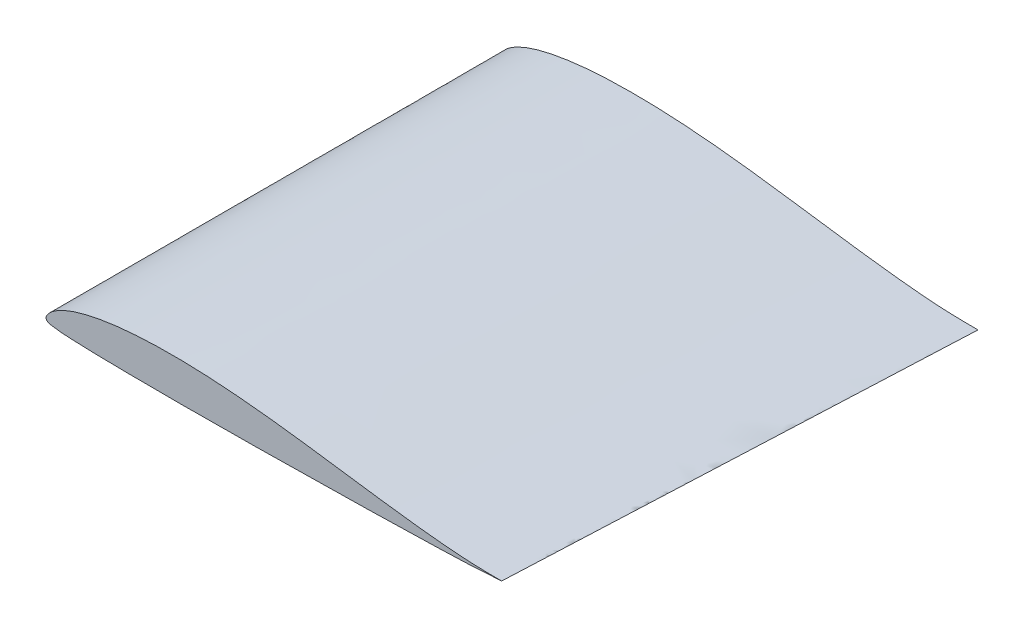
SolidWorks part; units mm, degrees
ref_plane "Front Plane" through (0, 0, 0) normal (0, 0, 1) x (1, 0, 0)
ref_plane "Top Plane" through (0, 0, 0) normal (0, 1, 0) x (1, 0, 0)
ref_plane "Right Plane" through (0, 0, 0) normal (1, 0, 0) x (0, 0, -1)
curve "Curve1"
  spline degree 3 poles (114.2372, -0.0369, 0) (115.1931, 0.0052, 0) (114.2229, -0.0046, 0) (113.4181, 0.0003, 0) (111.4454, 0.0187, 0) (108.9994, 0.0806, 0) (105.7801, 0.2031, 0) (101.978, 0.4673, 0) (97.6315, 0.881, 0) (92.8438, 1.4274, 0) (87.693, 2.0622, 0) (82.2613, 2.7949, 0) (76.6289, 3.5822, 0) (70.8754, 4.4083, 0) (65.0695, 5.2045, 0) (59.2726, 5.965, 0) (53.5354, 6.6121, 0) (47.902, 7.1479, 0) (42.4207, 7.5381, 0) (37.1257, 7.7843, 0) (32.0601, 7.8639, 0) (27.2609, 7.7997, 0) (22.7643, 7.5854, 0) (18.6066, 7.224, 0) (14.8196, 6.7174, 0) (11.4312, 6.1029, 0) (8.4633, 5.3595, 0) (5.93, 4.5232, 0) (3.8402, 3.6114, 0) (2.2031, 2.6805, 0) (0.9971, 1.7194, 0) (0.3061, 0.8447, 0) (-0.1539, -0.0168, 0) (0.4411, -0.7838, 0) (1.6303, -0.9762, 0) (3.345, -1.2471, 0) (5.7413, -1.3854, 0) (8.741, -1.531, 0) (12.3236, -1.6134, 0) (16.4261, -1.712, 0) (20.9966, -1.764, 0) (25.9799, -1.8041, 0) (31.3167, -1.8262, 0) (36.95, -1.8119, 0) (42.8101, -1.7838, 0) (48.8334, -1.73, 0) (54.9501, -1.6735, 0) (61.0935, -1.5952, 0) (67.1933, -1.4881, 0) (73.1769, -1.3978, 0) (78.98, -1.2712, 0) (84.5334, -1.153, 0) (89.7769, -1.0374, 0) (94.647, -0.905, 0) (99.0896, -0.7783, 0) (103.0556, -0.6463, 0) (106.4883, -0.5296, 0) (109.3913, -0.3707, 0) (111.629, -0.2442, 0) (113.4671, -0.0996, 0) (114.2372, -0.0369, 0) (115.1931, 0.0052, 0) (114.2229, -0.0046, 0) knots -0.013468 -0.006107 -0.001548 0 0.001545 0.006224 0.014036 0.024855 0.038644 0.055164 0.074045 0.09482 0.117223 0.140866 0.165395 0.190452 0.21571 0.240854 0.265734 0.290048 0.313714 0.336486 0.358293 0.37894 0.398278 0.416247 0.43266 0.44746 0.460566 0.472022 0.481784 0.489844 0.496307 0.501261 0.504695 0.507386 0.51219 0.519693 0.52998 0.542956 0.558414 0.576102 0.595805 0.617266 0.640272 0.664523 0.689804 0.715729 0.742084 0.768569 0.79484 0.82064 0.845625 0.869581 0.892164 0.91316 0.932311 0.949403 0.964221 0.976642 0.986532 0.993893 0.998452 1 1.001545 1.006224 1.014036 periodic
curve "Curve2"
  spline degree 3 poles (109.2695, -0.032, 0) (110.1862, 0.0049, 0) (109.2536, -0.0064, 0) (108.4853, 0.002, 0) (106.5995, 0.014, 0) (104.2599, 0.0712, 0) (101.179, 0.2009, 0) (97.5427, 0.452, 0) (93.3846, 0.8435, 0) (88.8052, 1.362, 0) (83.8804, 1.9786, 0) (78.6866, 2.6775, 0) (73.2995, 3.4307, 0) (67.7952, 4.2152, 0) (62.2412, 4.9847, 0) (56.6955, 5.6975, 0) (51.2078, 6.3228, 0) (45.8215, 6.8336, 0) (40.5778, 7.2116, 0) (35.5143, 7.4443, 0) (30.6685, 7.5275, 0) (26.0768, 7.4635, 0) (21.7757, 7.2552, 0) (17.7989, 6.9092, 0) (14.177, 6.4302, 0) (10.9351, 5.832, 0) (8.0947, 5.1223, 0) (5.6702, 4.3272, 0) (3.6698, 3.4606, 0) (2.1091, 2.5615, 0) (0.9527, 1.648, 0) (0.2925, 0.8103, 0) (-0.1445, -0.0134, 0) (0.4215, -0.7518, 0) (1.5614, -0.9277, 0) (3.1964, -1.1996, 0) (5.4899, -1.3252, 0) (8.3594, -1.4573, 0) (11.7865, -1.5532, 0) (15.712, -1.6328, 0) (20.0859, -1.6935, 0) (24.8533, -1.7305, 0) (29.9585, -1.7453, 0) (35.3441, -1.7366, 0) (40.949, -1.7075, 0) (46.7101, -1.6601, 0) (52.5621, -1.5957, 0) (58.4383, -1.5196, 0) (64.2724, -1.4291, 0) (69.9971, -1.3294, 0) (75.5481, -1.2224, 0) (80.8615, -1.1084, 0) (85.8767, -0.9906, 0) (90.5362, -0.8694, 0) (94.7848, -0.7467, 0) (98.5777, -0.6218, 0) (101.8584, -0.4962, 0) (104.6359, -0.3663, 0) (106.7737, -0.2243, 0) (108.5325, -0.0997, 0) (109.2695, -0.032, 0) (110.1862, 0.0049, 0) (109.2536, -0.0064, 0) knots -0.013463 -0.006118 -0.001552 0 0.001565 0.006239 0.014019 0.024861 0.03866 0.055174 0.074046 0.094837 0.117226 0.140856 0.165386 0.190451 0.215702 0.240867 0.265719 0.290052 0.313696 0.336484 0.35828 0.378929 0.398292 0.416236 0.43265 0.447456 0.460592 0.47203 0.481779 0.489853 0.496315 0.501246 0.504685 0.507404 0.512183 0.519673 0.529968 0.542948 0.5584 0.576099 0.595811 0.617283 0.64028 0.664535 0.689783 0.715733 0.742093 0.768567 0.794844 0.820639 0.845644 0.869584 0.892183 0.913178 0.932328 0.949411 0.96423 0.976629 0.986537 0.993882 0.998448 1 1.001565 1.006239 1.014019 periodic
sketch "Sketch1" plane through (0, 0, 0) normal (0, 0, 1) x (1, 0, 0)
  spline S0 degree 3 poles (114.2372, -0.0369) (115.1931, 0.0052) (114.2229, -0.0046) (113.4181, 0.0003) (111.4454, 0.0187) (108.9994, 0.0806) (105.7801, 0.2031) (101.978, 0.4673) (97.6315, 0.881) (92.8438, 1.4274) (87.693, 2.0622) (82.2613, 2.7949) (76.6289, 3.5822) (70.8754, 4.4083) (65.0695, 5.2045) (59.2726, 5.965) (53.5354, 6.6121) (47.902, 7.1479) (42.4207, 7.5381) (37.1257, 7.7843) (32.0601, 7.8639) (27.2609, 7.7997) (22.7643, 7.5854) (18.6066, 7.224) (14.8196, 6.7174) (11.4312, 6.1029) (8.4633, 5.3595) (5.93, 4.5232) (3.8402, 3.6114) (2.2031, 2.6805) (0.9971, 1.7194) (0.3061, 0.8447) (-0.1539, -0.0168) (0.4411, -0.7838) (1.6303, -0.9762) (3.345, -1.2471) (5.7413, -1.3854) (8.741, -1.531) (12.3236, -1.6134) (16.4261, -1.712) (20.9966, -1.764) (25.9799, -1.8041) (31.3167, -1.8262) (36.95, -1.8119) (42.8101, -1.7838) (48.8334, -1.73) (54.9501, -1.6735) (61.0935, -1.5952) (67.1933, -1.4881) (73.1769, -1.3978) (78.98, -1.2712) (84.5334, -1.153) (89.7769, -1.0374) (94.647, -0.905) (99.0896, -0.7783) (103.0556, -0.6463) (106.4883, -0.5296) (109.3913, -0.3707) (111.629, -0.2442) (113.4671, -0.0996) (114.2372, -0.0369) (115.1931, 0.0052) (114.2229, -0.0046) knots -0.013468 -0.006107 -0.001548 0 0.001545 0.006224 0.014036 0.024855 0.038644 0.055164 0.074045 0.09482 0.117223 0.140866 0.165395 0.190452 0.21571 0.240854 0.265734 0.290048 0.313714 0.336486 0.358293 0.37894 0.398278 0.416247 0.43266 0.44746 0.460566 0.472022 0.481784 0.489844 0.496307 0.501261 0.504695 0.507386 0.51219 0.519693 0.52998 0.542956 0.558414 0.576102 0.595805 0.617266 0.640272 0.664523 0.689804 0.715729 0.742084 0.768569 0.79484 0.82064 0.845625 0.869581 0.892164 0.91316 0.932311 0.949403 0.964221 0.976642 0.986532 0.993893 0.998452 1 1.001545 1.006224 1.014036 only from (115, 0) to (115, 0) construction
  spline S1 degree 3 poles (114.2372, -0.0369) (115.1931, 0.0052) (114.2229, -0.0046) (113.4181, 0.0003) (111.4454, 0.0187) (108.9994, 0.0806) (105.7801, 0.2031) (101.978, 0.4673) (97.6315, 0.881) (92.8438, 1.4274) (87.693, 2.0622) (82.2613, 2.7949) (76.6289, 3.5822) (70.8754, 4.4083) (65.0695, 5.2045) (59.2726, 5.965) (53.5354, 6.6121) (47.902, 7.1479) (42.4207, 7.5381) (37.1257, 7.7843) (32.0601, 7.8639) (27.2609, 7.7997) (22.7643, 7.5854) (18.6066, 7.224) (14.8196, 6.7174) (11.4312, 6.1029) (8.4633, 5.3595) (5.93, 4.5232) (3.8402, 3.6114) (2.2031, 2.6805) (0.9971, 1.7194) (0.3061, 0.8447) (-0.1539, -0.0168) (0.4411, -0.7838) (1.6303, -0.9762) (3.345, -1.2471) (5.7413, -1.3854) (8.741, -1.531) (12.3236, -1.6134) (16.4261, -1.712) (20.9966, -1.764) (25.9799, -1.8041) (31.3167, -1.8262) (36.95, -1.8119) (42.8101, -1.7838) (48.8334, -1.73) (54.9501, -1.6735) (61.0935, -1.5952) (67.1933, -1.4881) (73.1769, -1.3978) (78.98, -1.2712) (84.5334, -1.153) (89.7769, -1.0374) (94.647, -0.905) (99.0896, -0.7783) (103.0556, -0.6463) (106.4883, -0.5296) (109.3913, -0.3707) (111.629, -0.2442) (113.4671, -0.0996) (114.2372, -0.0369) (115.1931, 0.0052) (114.2229, -0.0046) knots -0.013468 -0.006107 -0.001548 0 0.001545 0.006224 0.014036 0.024855 0.038644 0.055164 0.074045 0.09482 0.117223 0.140866 0.165395 0.190452 0.21571 0.240854 0.265734 0.290048 0.313714 0.336486 0.358293 0.37894 0.398278 0.416247 0.43266 0.44746 0.460566 0.472022 0.481784 0.489844 0.496307 0.501261 0.504695 0.507386 0.51219 0.519693 0.52998 0.542956 0.558414 0.576102 0.595805 0.617266 0.640272 0.664523 0.689804 0.715729 0.742084 0.768569 0.79484 0.82064 0.845625 0.869581 0.892164 0.91316 0.932311 0.949403 0.964221 0.976642 0.986532 0.993893 0.998452 1 1.001545 1.006224 1.014036 only from (115, 0) to (115, 0)
ref_plane "Plane1" through (0, 0, 110) normal (0, 0, 1) x (1, 0, 0)
sketch "Sketch2" plane through (0, 0, 110) normal (0, 0, 1) x (1, 0, 0)
  spline S0 degree 3 poles (109.2695, -0.032) (110.1862, 0.0049) (109.2536, -0.0064) (108.4853, 0.002) (106.5995, 0.014) (104.2599, 0.0712) (101.179, 0.2009) (97.5427, 0.452) (93.3846, 0.8435) (88.8052, 1.362) (83.8804, 1.9786) (78.6866, 2.6775) (73.2995, 3.4307) (67.7952, 4.2152) (62.2412, 4.9847) (56.6955, 5.6975) (51.2078, 6.3228) (45.8215, 6.8336) (40.5778, 7.2116) (35.5143, 7.4443) (30.6685, 7.5275) (26.0768, 7.4635) (21.7757, 7.2552) (17.7989, 6.9092) (14.177, 6.4302) (10.9351, 5.832) (8.0947, 5.1223) (5.6702, 4.3272) (3.6698, 3.4606) (2.1091, 2.5615) (0.9527, 1.648) (0.2925, 0.8103) (-0.1445, -0.0134) (0.4215, -0.7518) (1.5614, -0.9277) (3.1964, -1.1996) (5.4899, -1.3252) (8.3594, -1.4573) (11.7865, -1.5532) (15.712, -1.6328) (20.0859, -1.6935) (24.8533, -1.7305) (29.9585, -1.7453) (35.3441, -1.7366) (40.949, -1.7075) (46.7101, -1.6601) (52.5621, -1.5957) (58.4383, -1.5196) (64.2724, -1.4291) (69.9971, -1.3294) (75.5481, -1.2224) (80.8615, -1.1084) (85.8767, -0.9906) (90.5362, -0.8694) (94.7848, -0.7467) (98.5777, -0.6218) (101.8584, -0.4962) (104.6359, -0.3663) (106.7737, -0.2243) (108.5325, -0.0997) (109.2695, -0.032) (110.1862, 0.0049) (109.2536, -0.0064) knots -0.013463 -0.006118 -0.001552 0 0.001565 0.006239 0.014019 0.024861 0.03866 0.055174 0.074046 0.094837 0.117226 0.140856 0.165386 0.190451 0.215702 0.240867 0.265719 0.290052 0.313696 0.336484 0.35828 0.378929 0.398292 0.416236 0.43265 0.447456 0.460592 0.47203 0.481779 0.489853 0.496315 0.501246 0.504685 0.507404 0.512183 0.519673 0.529968 0.542948 0.5584 0.576099 0.595811 0.617283 0.64028 0.664535 0.689783 0.715733 0.742093 0.768567 0.794844 0.820639 0.845644 0.869584 0.892183 0.913178 0.932328 0.949411 0.96423 0.976629 0.986537 0.993882 0.998448 1 1.001565 1.006239 1.014019 only from (110, 0) to (110, 0) construction
  spline S1 degree 3 poles (109.2695, -0.032) (110.1862, 0.0049) (109.2536, -0.0064) (108.4853, 0.002) (106.5995, 0.014) (104.2599, 0.0712) (101.179, 0.2009) (97.5427, 0.452) (93.3846, 0.8435) (88.8052, 1.362) (83.8804, 1.9786) (78.6866, 2.6775) (73.2995, 3.4307) (67.7952, 4.2152) (62.2412, 4.9847) (56.6955, 5.6975) (51.2078, 6.3228) (45.8215, 6.8336) (40.5778, 7.2116) (35.5143, 7.4443) (30.6685, 7.5275) (26.0768, 7.4635) (21.7757, 7.2552) (17.7989, 6.9092) (14.177, 6.4302) (10.9351, 5.832) (8.0947, 5.1223) (5.6702, 4.3272) (3.6698, 3.4606) (2.1091, 2.5615) (0.9527, 1.648) (0.2925, 0.8103) (-0.1445, -0.0134) (0.4215, -0.7518) (1.5614, -0.9277) (3.1964, -1.1996) (5.4899, -1.3252) (8.3594, -1.4573) (11.7865, -1.5532) (15.712, -1.6328) (20.0859, -1.6935) (24.8533, -1.7305) (29.9585, -1.7453) (35.3441, -1.7366) (40.949, -1.7075) (46.7101, -1.6601) (52.5621, -1.5957) (58.4383, -1.5196) (64.2724, -1.4291) (69.9971, -1.3294) (75.5481, -1.2224) (80.8615, -1.1084) (85.8767, -0.9906) (90.5362, -0.8694) (94.7848, -0.7467) (98.5777, -0.6218) (101.8584, -0.4962) (104.6359, -0.3663) (106.7737, -0.2243) (108.5325, -0.0997) (109.2695, -0.032) (110.1862, 0.0049) (109.2536, -0.0064) knots -0.013463 -0.006118 -0.001552 0 0.001565 0.006239 0.014019 0.024861 0.03866 0.055174 0.074046 0.094837 0.117226 0.140856 0.165386 0.190451 0.215702 0.240867 0.265719 0.290052 0.313696 0.336484 0.35828 0.378929 0.398292 0.416236 0.43265 0.447456 0.460592 0.47203 0.481779 0.489853 0.496315 0.501246 0.504685 0.507404 0.512183 0.519673 0.529968 0.542948 0.5584 0.576099 0.595811 0.617283 0.64028 0.664535 0.689783 0.715733 0.742093 0.768567 0.794844 0.820639 0.845644 0.869584 0.892183 0.913178 0.932328 0.949411 0.96423 0.976629 0.986537 0.993882 0.998448 1 1.001565 1.006239 1.014019 only from (110, 0) to (110, 0)
loft "Loft1" add profiles "Sketch1", "Sketch2"
sketch3d "3DSketch1"
  line L0 (109.958, 0.0012, 110) -> (-0.0041, 0.0606, 110)
  spline S0 degree 3 poles (-0.0041, 0.0606, 110) (0.0315, -1.565, -338.6935) (-0.069, 4.911, 79.3992) (0.056, 12.511, -112.5454) knots 0 0 0 0 1 1 1 1
  spline S1 degree 3 poles (109.2695, -0.032, 110) (110.1862, 0.0049, 110) (109.2536, -0.0064, 110) (108.4853, 0.002, 110) (106.5995, 0.014, 110) (104.2599, 0.0712, 110) (101.179, 0.2009, 110) (97.5427, 0.452, 110) (93.3846, 0.8435, 110) (88.8052, 1.362, 110) (83.8804, 1.9786, 110) (78.6866, 2.6775, 110) (73.2995, 3.4307, 110) (67.7952, 4.2152, 110) (62.2412, 4.9847, 110) (56.6955, 5.6975, 110) (51.2078, 6.3228, 110) (45.8215, 6.8336, 110) (40.5778, 7.2116, 110) (35.5143, 7.4443, 110) (30.6685, 7.5275, 110) (26.0768, 7.4635, 110) (21.7757, 7.2552, 110) (17.7989, 6.9092, 110) (14.177, 6.4302, 110) (10.9351, 5.832, 110) (8.0947, 5.1223, 110) (5.6702, 4.3272, 110) (3.6698, 3.4606, 110) (2.1091, 2.5615, 110) (0.9527, 1.648, 110) (0.2925, 0.8103, 110) (-0.1445, -0.0134, 110) (0.4215, -0.7518, 110) (1.5614, -0.9277, 110) (3.1964, -1.1996, 110) (5.4899, -1.3252, 110) (8.3594, -1.4573, 110) (11.7865, -1.5532, 110) (15.712, -1.6328, 110) (20.0859, -1.6935, 110) (24.8533, -1.7305, 110) (29.9585, -1.7453, 110) (35.3441, -1.7366, 110) (40.949, -1.7075, 110) (46.7101, -1.6601, 110) (52.5621, -1.5957, 110) (58.4383, -1.5196, 110) (64.2724, -1.4291, 110) (69.9971, -1.3294, 110) (75.5481, -1.2224, 110) (80.8615, -1.1084, 110) (85.8767, -0.9906, 110) (90.5362, -0.8694, 110) (94.7848, -0.7467, 110) (98.5777, -0.6218, 110) (101.8584, -0.4962, 110) (104.6359, -0.3663, 110) (106.7737, -0.2243, 110) (108.5325, -0.0997, 110) (109.2695, -0.032, 110) (110.1862, 0.0049, 110) (109.2536, -0.0064, 110) knots -0.013463 -0.006118 -0.001552 0 0.001565 0.006239 0.014019 0.024861 0.03866 0.055174 0.074046 0.094837 0.117226 0.140856 0.165386 0.190451 0.215702 0.240867 0.265719 0.290052 0.313696 0.336484 0.35828 0.378929 0.398292 0.416236 0.43265 0.447456 0.460592 0.47203 0.481779 0.489853 0.496315 0.501246 0.504685 0.507404 0.512183 0.519673 0.529968 0.542948 0.5584 0.576099 0.595811 0.617283 0.64028 0.664535 0.689783 0.715733 0.742093 0.768567 0.794844 0.820639 0.845644 0.869584 0.892183 0.913178 0.932328 0.949411 0.96423 0.976629 0.986537 0.993882 0.998448 1 1.001565 1.006239 1.014019 only from (110, 0, 110) to (110, 0, 110) construction
  spline S2 degree 3 poles (109.2536, -0.0064, 110) (110.1862, 0.0049, 110) (109.2695, -0.032, 110) (108.5325, -0.0997, 110) (106.7737, -0.2243, 110) (104.6359, -0.3663, 110) (101.8584, -0.4962, 110) (98.5777, -0.6218, 110) (94.7848, -0.7467, 110) (90.5362, -0.8694, 110) (85.8767, -0.9906, 110) (80.8615, -1.1084, 110) (75.5481, -1.2224, 110) (69.9971, -1.3294, 110) (64.2724, -1.4291, 110) (58.4383, -1.5196, 110) (52.5621, -1.5957, 110) (46.7101, -1.6601, 110) (40.949, -1.7075, 110) (35.3441, -1.7366, 110) (29.9585, -1.7453, 110) (24.8533, -1.7305, 110) (20.0859, -1.6935, 110) (15.712, -1.6328, 110) (11.7865, -1.5532, 110) (8.3594, -1.4573, 110) (5.4899, -1.3252, 110) (3.1964, -1.1996, 110) (1.5614, -0.9277, 110) (0.4215, -0.7518, 110) (-0.1445, -0.0134, 110) (0.2925, 0.8103, 110) (0.9527, 1.648, 110) (2.1091, 2.5615, 110) (3.6698, 3.4606, 110) (5.6702, 4.3272, 110) (8.0947, 5.1223, 110) (10.9351, 5.832, 110) (14.177, 6.4302, 110) (17.7989, 6.9092, 110) (21.7757, 7.2552, 110) (26.0768, 7.4635, 110) (30.6685, 7.5275, 110) (35.5143, 7.4443, 110) (40.5778, 7.2116, 110) (45.8215, 6.8336, 110) (51.2078, 6.3228, 110) (56.6955, 5.6975, 110) (62.2412, 4.9847, 110) (67.7952, 4.2152, 110) (73.2995, 3.4307, 110) (78.6866, 2.6775, 110) (83.8804, 1.9786, 110) (88.8052, 1.362, 110) (93.3846, 0.8435, 110) (97.5427, 0.452, 110) (101.179, 0.2009, 110) (104.2599, 0.0712, 110) (106.5995, 0.014, 110) (108.4853, 0.002, 110) (109.2536, -0.0064, 110) (110.1862, 0.0049, 110) (109.2695, -0.032, 110) knots -0.014019 -0.006239 -0.001565 0 0.001552 0.006118 0.013463 0.023371 0.03577 0.050589 0.067672 0.086822 0.107817 0.130416 0.154356 0.179361 0.205156 0.231433 0.257907 0.284267 0.310217 0.335465 0.35972 0.382717 0.404189 0.423901 0.4416 0.457052 0.470032 0.480327 0.487817 0.492596 0.495315 0.498754 0.503685 0.510147 0.518221 0.52797 0.539408 0.552544 0.56735 0.583764 0.601708 0.621071 0.64172 0.663516 0.686304 0.709948 0.734281 0.759133 0.784298 0.809549 0.834614 0.859144 0.882774 0.905163 0.925954 0.944826 0.96134 0.975139 0.985981 0.993761 0.998435 1 1.001552 1.006118 1.013463 only from (110, 0, 110) to (110, 0, 110) construction
  spline S3 degree 3 poles (0.056, 12.511, -112.5454) (36.7587, 17.2094, -112.9091) (72.3737, 14.4641, -114.505) (106.8822, 2.4299, -108.2168) knots 0 0 0 0 1 1 1 1
  spline S4 degree 2 poles (109.958, 0.0012, 110) (178.3212, -44.3264, -37.5467) (106.8822, 2.4299, -108.2168) knots 0 0 0 1 1 1
  spline S5 degree 3 poles (-0.0041, 0.0606, 110) (-0.0059, 0.0222, 110) (0.0056, -0.2093, 110) (0.4215, -0.7518, 110) (1.5614, -0.9277, 110) (3.1964, -1.1996, 110) (5.4899, -1.3252, 110) (8.3594, -1.4573, 110) (11.7865, -1.5532, 110) (15.712, -1.6328, 110) (20.0859, -1.6935, 110) (24.8533, -1.7305, 110) (29.9585, -1.7453, 110) (35.3441, -1.7366, 110) (40.949, -1.7075, 110) (46.7101, -1.6601, 110) (52.5621, -1.5957, 110) (58.4383, -1.5196, 110) (64.2724, -1.4291, 110) (69.9971, -1.3294, 110) (75.5481, -1.2224, 110) (80.8615, -1.1084, 110) (85.8767, -0.9906, 110) (90.5362, -0.8694, 110) (94.7848, -0.7467, 110) (98.5777, -0.6218, 110) (101.8584, -0.4962, 110) (104.6359, -0.3663, 110) (106.7737, -0.2243, 110) (108.5325, -0.0997, 110) (109.2695, -0.032, 110) (110.1862, 0.0049, 110) (109.2536, -0.0064, 110) (108.8452, -0.0019, 110) (108.45, 0.0014, 110) (108.3661, 0.0021, 110) knots 0.504147 0.504147 0.504147 0.504147 0.504685 0.507404 0.512183 0.519673 0.529968 0.542948 0.5584 0.576099 0.595811 0.617283 0.64028 0.664535 0.689783 0.715733 0.742093 0.768567 0.794844 0.820639 0.845644 0.869584 0.892183 0.913178 0.932328 0.949411 0.96423 0.976629 0.986537 0.993882 0.998448 1 1.001565 1.006239 1.007451 1.007451 1.007451 1.007451
sketch "Sketch4" plane through (0, 0, 0) normal (0, 0, -1) x (-1, 0, 0)
  circle A0 centre (-10.5, 2) radius 2.6
  circle A1 centre (-57, 2.1) radius 3.1
  dimension "D1" = 5.2
  dimension "D2" = 6.2
  dimension "D3" = 10.5
  dimension "D4" = 2
  dimension "D5" = 2.1
  dimension "D6" = 57
extrude "Cut-Extrude1" cut sketch "Sketch4" against normal blind 5.2
sketch "Sketch5" plane through (0, 0, 0) normal (0, 0, -1) x (-1, 0, 0)
  line L1 (-25.95, 5.8) -> (-16.05, 5.8)
  line L2 (-25.95, 5.8) -> (-25.95, -0.2)
  line L3 (-25.95, -0.2) -> (-16.05, -0.2)
  line L4 (-16.05, 5.8) -> (-16.05, -0.2)
  line L5 (-25.95, 5.8) -> (-16.05, -0.2) construction
  line L6 (-25.95, -0.2) -> (-16.05, 5.8) construction
  line L7 (-50.75, 6) -> (-41.25, 6)
  line L8 (-50.75, 6) -> (-50.75, 0)
  line L9 (-50.75, 0) -> (-41.25, 0)
  line L10 (-41.25, 6) -> (-41.25, 0)
  line L11 (-50.75, 6) -> (-41.25, 0) construction
  line L12 (-50.75, 0) -> (-41.25, 6) construction
  point P0 (-21, 2.8)
  point P5 (-46, 3)
  dimension "D1" = 6
  dimension "D2" = 9.9
  dimension "D3" = 9.5
  dimension "D4" = 6
  dimension "D5" = 46
  dimension "D6" = 3
  dimension "D7" = 2.8
  dimension "D8" = 21
extrude "Cut-Extrude2" cut sketch "Sketch5" against normal blind 70
fillet "Fillet3" radius 2 4 edges at (41.25, 6, 35) (50.75, 6, 35) (16.05, 5.8, 35) (25.95, 5.8, 35)
chamfer "Chamfer1" distance 1 angle 50 4 edges at (41.25, 0, 35) (50.75, 0, 35) (16.05, -0.2, 35) (25.95, -0.2, 35)
sketch "Sketch6" plane through (0, 0, 0) normal (0, 0, -1) x (-1, 0, 0)
  line L0 (-63.4623, 3.7932) -> (-63.4623, 0.2352)
  line L3 (-63.4623, 0.2352) -> (-89.8656, 0.2352)
  line L4 (-89.8656, 0.2352) -> (-63.4623, 3.7932)
  spline S1 degree 3 poles (-114.2229, -0.0046) (-115.1931, 0.0052) (-114.2372, -0.0369) (-113.4671, -0.0996) (-111.629, -0.2442) (-109.3913, -0.3707) (-106.4883, -0.5296) (-103.0556, -0.6463) (-99.0896, -0.7783) (-94.647, -0.905) (-89.7769, -1.0374) (-84.5334, -1.153) (-78.98, -1.2712) (-73.1769, -1.3978) (-67.1933, -1.4881) (-61.0935, -1.5952) (-54.9501, -1.6735) (-48.8334, -1.73) (-42.8101, -1.7838) (-36.95, -1.8119) (-31.3167, -1.8262) (-25.9799, -1.8041) (-20.9966, -1.764) (-16.4261, -1.712) (-12.3236, -1.6134) (-8.741, -1.531) (-5.7413, -1.3854) (-3.345, -1.2471) (-1.6303, -0.9762) (-0.4411, -0.7838) (0.1539, -0.0168) (-0.3061, 0.8447) (-0.9971, 1.7194) (-2.2031, 2.6805) (-3.8402, 3.6114) (-5.93, 4.5232) (-8.4633, 5.3595) (-11.4312, 6.1029) (-14.8196, 6.7174) (-18.6066, 7.224) (-22.7643, 7.5854) (-27.2609, 7.7997) (-32.0601, 7.8639) (-37.1257, 7.7843) (-42.4207, 7.5381) (-47.902, 7.1479) (-53.5354, 6.6121) (-59.2726, 5.965) (-65.0695, 5.2045) (-70.8754, 4.4083) (-76.6289, 3.5822) (-82.2613, 2.7949) (-87.693, 2.0622) (-92.8438, 1.4274) (-97.6315, 0.881) (-101.978, 0.4673) (-105.7801, 0.2031) (-108.9994, 0.0806) (-111.4454, 0.0187) (-113.4181, 0.0003) (-114.2229, -0.0046) (-115.1931, 0.0052) (-114.2372, -0.0369) knots -0.014036 -0.006224 -0.001545 0 0.001548 0.006107 0.013468 0.023358 0.035779 0.050597 0.067689 0.08684 0.107836 0.130419 0.154375 0.17936 0.20516 0.231431 0.257916 0.284271 0.310196 0.335477 0.359728 0.382734 0.404195 0.423898 0.441586 0.457044 0.47002 0.480307 0.48781 0.492614 0.495305 0.498739 0.503693 0.510156 0.518216 0.527978 0.539434 0.55254 0.56734 0.583753 0.601722 0.62106 0.641707 0.663514 0.686286 0.709952 0.734266 0.759146 0.78429 0.809548 0.834605 0.859134 0.882777 0.90518 0.925955 0.944836 0.961356 0.975145 0.985964 0.993776 0.998455 1 1.001548 1.006107 1.013468 only from (-115, 0) to (-115, 0) construction
  spline S2 degree 3 poles (-114.2229, -0.0046) (-115.1931, 0.0052) (-114.2372, -0.0369) (-113.4671, -0.0996) (-111.629, -0.2442) (-109.3913, -0.3707) (-106.4883, -0.5296) (-103.0556, -0.6463) (-99.0896, -0.7783) (-94.647, -0.905) (-89.7769, -1.0374) (-84.5334, -1.153) (-78.98, -1.2712) (-73.1769, -1.3978) (-67.1933, -1.4881) (-61.0935, -1.5952) (-54.9501, -1.6735) (-48.8334, -1.73) (-42.8101, -1.7838) (-36.95, -1.8119) (-31.3167, -1.8262) (-25.9799, -1.8041) (-20.9966, -1.764) (-16.4261, -1.712) (-12.3236, -1.6134) (-8.741, -1.531) (-5.7413, -1.3854) (-3.345, -1.2471) (-1.6303, -0.9762) (-0.4411, -0.7838) (0.1539, -0.0168) (-0.3061, 0.8447) (-0.9971, 1.7194) (-2.2031, 2.6805) (-3.8402, 3.6114) (-5.93, 4.5232) (-8.4633, 5.3595) (-11.4312, 6.1029) (-14.8196, 6.7174) (-18.6066, 7.224) (-22.7643, 7.5854) (-27.2609, 7.7997) (-32.0601, 7.8639) (-37.1257, 7.7843) (-42.4207, 7.5381) (-47.902, 7.1479) (-53.5354, 6.6121) (-59.2726, 5.965) (-65.0695, 5.2045) (-70.8754, 4.4083) (-76.6289, 3.5822) (-82.2613, 2.7949) (-87.693, 2.0622) (-92.8438, 1.4274) (-97.6315, 0.881) (-101.978, 0.4673) (-105.7801, 0.2031) (-108.9994, 0.0806) (-111.4454, 0.0187) (-113.4181, 0.0003) (-114.2229, -0.0046) (-115.1931, 0.0052) (-114.2372, -0.0369) knots -0.014036 -0.006224 -0.001545 0 0.001548 0.006107 0.013468 0.023358 0.035779 0.050597 0.067689 0.08684 0.107836 0.130419 0.154375 0.17936 0.20516 0.231431 0.257916 0.284271 0.310196 0.335477 0.359728 0.382734 0.404195 0.423898 0.441586 0.457044 0.47002 0.480307 0.48781 0.492614 0.495305 0.498739 0.503693 0.510156 0.518216 0.527978 0.539434 0.55254 0.56734 0.583753 0.601722 0.62106 0.641707 0.663514 0.686286 0.709952 0.734266 0.759146 0.78429 0.809548 0.834605 0.859134 0.882777 0.90518 0.925955 0.944836 0.961356 0.975145 0.985964 0.993776 0.998455 1 1.001548 1.006107 1.013468 only from (-115, 0) to (-115, 0)
  point P0 (-89.8656, 0.2352)
extrude "Cut-Extrude3" cut sketch "Sketch6" against normal blind 90.2 contours L4 L0 L3
fillet "Fillet4" radius 0.2 1 edges at (89.8656, 0.2352, 45.1)
fillet "Fillet5" radius 0.5 1 edges at (63.4623, 3.7932, 45.1)
chamfer "Chamfer2" distance 1 angle 45 1 edges at (63.4623, 0.2352, 45.1)
